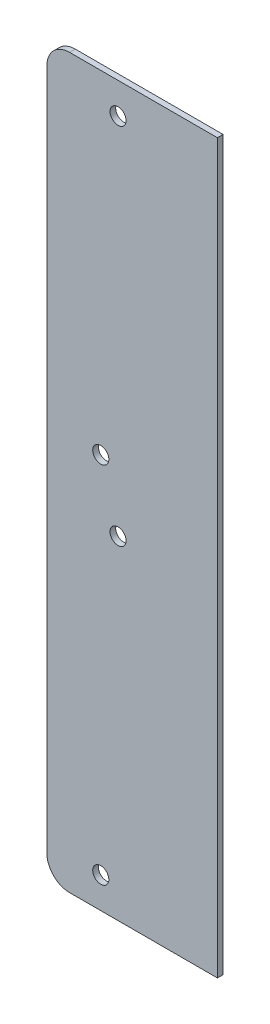
SolidWorks part; units mm, degrees
material "ASTM A36 Steel"
ref_plane "X-Y Datum" through (0, 0, 0) normal (0, 0, 1) x (1, 0, 0)
ref_plane "X-Z Datum" through (0, 0, 0) normal (0, 1, 0) x (1, 0, 0)
ref_plane "Y-Z Datum" through (0, 0, 0) normal (1, 0, 0) x (0, 0, -1)
sketch "Sketch1" plane through (0, 0, 0) normal (0, 0, 1) x (1, 0, 0)
  line L0 (-2.413, -42.164) -> (2.413, -42.164) construction
  line L1 (-17.4625, 50.8) -> (17.4625, 50.8)
  line L2 (-17.4625, 50.8) -> (-17.4625, -50.8)
  line L3 (-17.4625, -50.8) -> (17.4625, -50.8)
  line L4 (17.4625, 50.8) -> (17.4625, -50.8)
  line L5 (-17.4625, 50.8) -> (17.4625, -50.8) construction
  line L6 (-17.4625, -50.8) -> (17.4625, 50.8) construction
  line L7 (2.413, -42.164) -> (2.413, 42.164) construction
  point P0 (0, 0)
  point P6 (2.413, 42.164)
  point P7 (-2.413, -42.164)
  point P10 (2.413, 0)
  point P16 (0, -42.164)
  dimension "D1" = 34.925
  dimension "D2" = 101.6
  dimension "D3" = 84.328
  dimension "D4" = 4.826
extrude "Boss-Extrude1" add sketch "Sketch1" along normal blind 1.5875
hole_wizard "M4 Clearance Hole1" positions "Sketch3" profile "Sketch4" hole size "M4" standard "ANSI Metric" end condition through all
sketch "Sketch3" plane through (0, 0, 1.5875) normal (0, 0, 1) x (1, 0, 0)
  point P0 (-2.413, -42.164)
  point P3 (2.413, 42.164)
sketch "Sketch4" plane through (-2.413, -42.164, 1.5875) normal (1, 0, 0) x (0, -1, 0)
  line L0 (0, 0) -> (0, 1.5875)
  line L1 (0, 1.5875) -> (2.25, 1.5875)
  line L2 (2.25, 1.5875) -> (2.25, 0)
  line L5 (2.25, 0) -> (0, 0)
  line L11 (0, -6.35) -> (0, 107.95) construction
  dimension "Thru Hole Dia." = 4.5
  dimension "Thru Hole Depth" = 1.5875
sketch "Sketch8" plane through (0, 0, 1.5875) normal (0, 0, 1) x (1, 0, 0)
  line L1 (-17.4625, 50.8) -> (17.4625, 50.8)
  line L2 (-17.4625, 50.8) -> (-17.4625, 152.4)
  line L3 (-17.4625, 152.4) -> (17.4625, 152.4)
  line L4 (17.4625, 50.8) -> (-17.4625, 50.8)
  line L5 (17.4625, -50.8) -> (17.4625, 50.8)
  line L6 (-17.4625, -50.8) -> (17.4625, -50.8)
  line L7 (-17.4625, 50.8) -> (-17.4625, -50.8)
  line L8 (17.4625, 50.8) -> (-17.4625, 50.8)
  line L9 (17.4625, -50.8) -> (17.4625, 50.8)
  line L10 (-17.4625, -50.8) -> (17.4625, -50.8)
  line L11 (-17.4625, 50.8) -> (-17.4625, -50.8)
  line L12 (17.4625, 50.8) -> (17.4625, 152.4)
  circle A0 centre (-2.413, -42.164) radius 2.25 construction
  circle A1 centre (2.413, 42.164) radius 2.25 construction
  circle A2 centre (-2.413, -42.164) radius 2.25
  circle A3 centre (2.413, 42.164) radius 2.25
  circle A6 centre (2.413, 143.764) radius 2.25
  circle A7 centre (-2.413, 59.436) radius 2.25
  dimension "D2" = 101.6
  dimension "D1" = 0
extrude "Boss-Extrude4" add sketch "Sketch8" against normal blind 1.5875
sketch "Sketch6" plane through (0, 0, 1.5875) normal (0, 0, 1) x (1, 0, 0)
  line L0 (17.4625, -50.8) -> (17.4625, 152.4) construction
  line L1 (-17.4625, -50.8) -> (17.4625, -50.8)
  line L2 (-17.4625, -50.8) -> (-17.4625, -66.675)
  line L3 (-17.4625, -66.675) -> (17.4625, -66.675)
  line L4 (17.4625, -50.8) -> (17.4625, -66.675)
  dimension "D1" = 15.875
extrude "Boss-Extrude3" [suppressed] add sketch "Sketch6" against normal blind 3.175
sketch "Sketch9" plane through (0, 0, 1.5875) normal (0, 0, 1) x (1, 0, 0)
  line L0 (-17.4625, -50.8) -> (17.4625, -50.8) construction
  line L1 (17.4625, 152.4) -> (30.1625, 152.4)
  line L2 (17.4625, 152.4) -> (17.4625, -50.8)
  line L3 (17.4625, -50.8) -> (30.1625, -50.8)
  line L4 (30.1625, 152.4) -> (30.1625, -50.8)
  dimension "D1" = 12.7
extrude "Boss-Extrude5" add sketch "Sketch9" against normal blind 1.5875
fillet "Fillet1" radius 6.35 2 edges at (-17.4625, -50.8, 0.7937) (-17.4625, 152.4, 0.7937)
